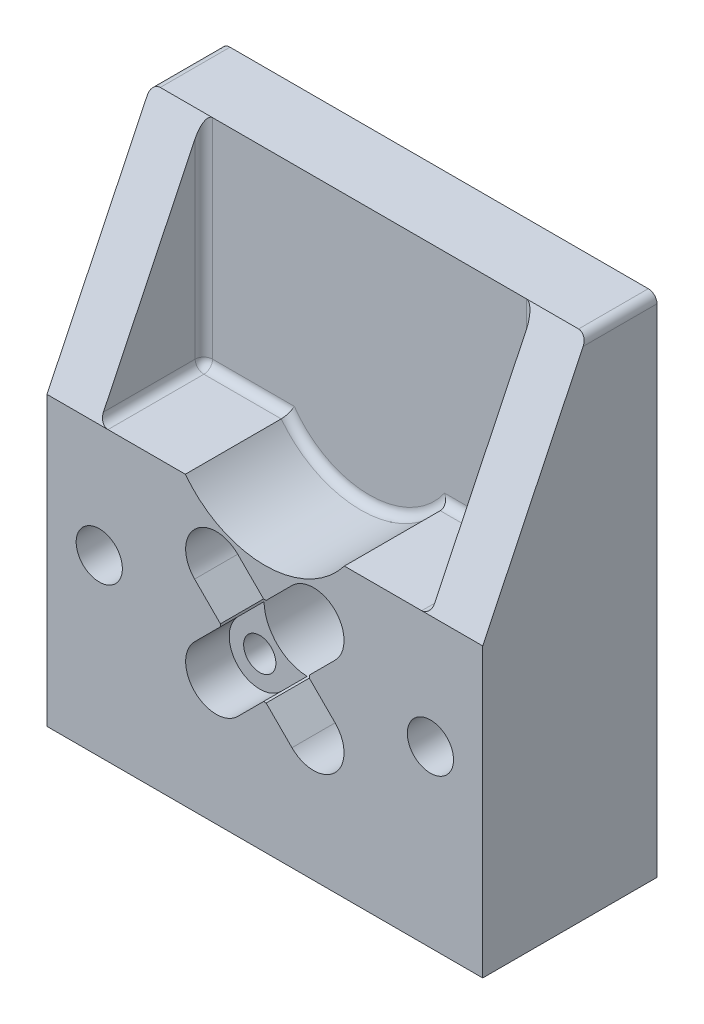
SolidWorks part; units mm, degrees
ref_plane "Front Plane" through (0, 0, 0) normal (0, 0, 1) x (1, 0, 0)
ref_plane "Top Plane" through (0, 0, 0) normal (0, 1, 0) x (1, 0, 0)
ref_plane "Right Plane" through (0, 0, 0) normal (1, 0, 0) x (0, 0, -1)
sketch "Sketch1" plane through (0, 0, 0) normal (0, 1, 0) x (1, 0, 0)
  line L1 (0, 0) -> (50, 0)
  line L2 (0, 0) -> (0, 20)
  line L3 (0, 20) -> (50, 20)
  line L4 (50, 0) -> (50, 20)
  dimension "D1" = 50
  dimension "D2" = 20
extrude "Boss-Extrude1" add sketch "Sketch1" along normal blind 33
sketch "Sketch2" plane through (0, 0, 0) normal (0, 0, 1) x (1, 0, 0)
  line L0 (25, 0) -> (25, 20) construction
  line L1 (0, 0) -> (50, 0) construction
  line L2 (6, 20) -> (44, 20) construction
  circle A0 centre (6, 20) radius 2.65
  circle A1 centre (44, 20) radius 2.65
  point P7 (25, 20)
  dimension "D1" = 5.3
  dimension "D2" = 38
  dimension "D3" = 20
extrude "Cut-Extrude1" cut sketch "Sketch2" against normal through all
sketch "Sketch3" plane through (0, 0, 0) normal (0, 0, 1) x (1, 0, 0)
  circle A0 centre (44, 20) radius 2.65 construction
  circle A1 centre (6, 20) radius 2.65 construction
  circle A2 centre (44, 20) radius 2.65 construction
  circle A3 centre (6, 20) radius 2.65 construction
  circle A5 centre (25, 20) radius 5.1
  circle A6 centre (25, 20) radius 11.15
  circle A10 centre (19.4139, 25.5861) radius 1.85
  circle A11 centre (30.5861, 25.5861) radius 1.85
  circle A12 centre (30.5861, 14.4139) radius 1.85
  circle A13 centre (19.4139, 14.4139) radius 1.85
  dimension "D1" = 3.7
  dimension "D2" = 22.3
  dimension "D3" = 3.7
  dimension "D4" = 3.7
  dimension "D5" = 3.7
sketch "Sketch7" plane through (0, 33, 0) normal (0, 1, 0) x (1, 0, 0)
  line L0 (0, 20) -> (0, 0) construction
  line L2 (50, 0) -> (50, 20)
  line L4 (0, 0) -> (0, 20)
  line L12 (50, 20) -> (0, 20)
  line L13 (50, 0) -> (44, 0)
  line L14 (0, 0) -> (50, 0) construction
  line L15 (44, 0) -> (44, 12)
  line L16 (44, 12) -> (6, 12)
  line L17 (6, 12) -> (6, 0)
  line L18 (6, 0) -> (0, 0)
  dimension "D1" = 6
  dimension "D2" = 8
extrude "Boss-Extrude2" add sketch "Sketch7" along normal blind 25
sketch "Sketch8" plane through (0, 0, 0) normal (-1, 0, 0) x (0, 0, 1)
  line L1 (0, 58) -> (0, 33) construction
  line L2 (-12, 58) -> (0, 58) construction
  line L3 (0, 58) -> (0, 33)
  line L4 (-12, 58) -> (0, 58)
  line L5 (-12, 58) -> (0, 33)
extrude "Cut-Extrude8" cut sketch "Sketch8" against normal through all
sketch "Sketch10" plane through (0, 0, -12) normal (0, 0, 1) x (1, 0, 0)
  line L0 (25, 58) -> (25, 40) construction
  line L1 (6, 58) -> (44, 58) construction
  circle A0 centre (25, 40) radius 11.5
  dimension "D2" = 23
  dimension "D1" = 18
extrude "Cut-Extrude10" cut sketch "Sketch10" along normal through all
fillet "Fillet1" radius 1 9 edges at (44, 33, -6) (6, 33, -6) (6, 45.5, -12) (44, 45.5, -12) (10.9379, 33, -12) (39.0621, 33, -12) (0, 58, -16) (50, 58, -16) (25, 28.5, -12)
ref_plane "Plane4" through (0, 0, 0) normal (0, 0, 1) x (1, 0, 0)
extrude "Cut-Extrude11" cut sketch "Sketch3" against normal through all contours A10 | A5 | A11 | A12 | A13
ref_plane "Plane5" through (0, 0, -20) normal (0, 0, -1) x (-1, 0, 0)
sketch "Sketch11" plane through (0, 0, -20) normal (0, 0, -1) x (-1, 0, 0)
  line L0 (-21.816, 16.016) -> (-25, 20)
  circle A0 centre (-25, 20) radius 5.1 construction
  circle A1 centre (-25, 20) radius 11.15
  dimension "D1" = 22.3
extrude "Cut-Extrude12" cut sketch "Sketch11" against normal blind 3.8
sketch "Sketch12" plane through (0, 0, 0) normal (0, 0, 1) x (1, 0, 0)
  line L0 (19.4139, 14.4139) -> (30.5861, 25.5861)
  line L5 (19.4139, 25.5861) -> (30.5861, 14.4139)
  line L6 (15.0302, 21.2025) -> (23.98, 30.1523)
  line L7 (16.939, 23.1113) -> (30.3935, 9.6568)
  line L8 (21.8887, 28.061) -> (35.3432, 14.6065)
  line L9 (35.1101, 21.0622) -> (27.2192, 28.9531)
  line L10 (28.1113, 28.061) -> (14.6568, 14.6065)
  line L11 (33.061, 23.1113) -> (19.6065, 9.6568)
  circle A0 centre (25, 20) radius 5.1
  circle A1 centre (25, 20) radius 11.665
  circle A2 centre (19.4139, 25.5861) radius 3.5
  circle A3 centre (30.5861, 25.5861) radius 3.5
  circle A4 centre (30.5861, 14.4139) radius 3.5
  circle A5 centre (19.4139, 14.4139) radius 3.5
  dimension "D1" = 7
  dimension "D2" = 7
  dimension "D3" = 7
  dimension "D4" = 7
  dimension "D5" = 10.2
extrude "Cut-Extrude14" cut sketch "Sketch12" against normal blind 5
